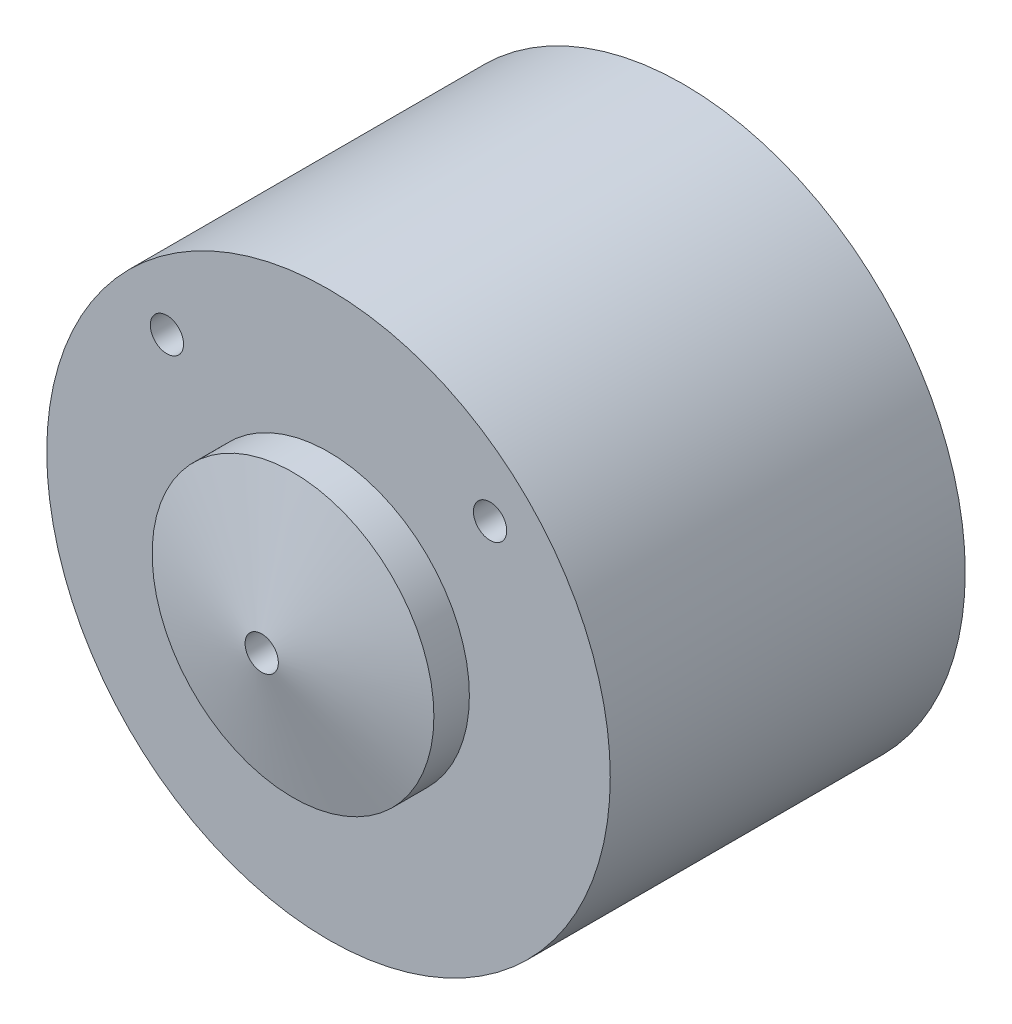
SolidWorks part; units mm, degrees
ref_plane "Спереди" through (0, 0, 0) normal (0, 0, 1) x (1, 0, 0)
ref_plane "Сверху" through (0, 0, 0) normal (0, 1, 0) x (1, 0, 0)
ref_plane "Справа" through (0, 0, 0) normal (1, 0, 0) x (0, 0, -1)
sketch "Эскиз1" plane through (0, 0, 0) normal (0, 0, 1) x (1, 0, 0)
  circle A0 centre (0, 0) radius 12.7
  dimension "D1" = 25.4
extrude "Бобышка-Вытянуть1" add sketch "Эскиз1" along normal blind 16
sketch "Эскиз2" plane through (0, 0, 16) normal (0, 0, 1) x (1, 0, 0)
  circle A0 centre (0, 0) radius 6.35
  dimension "D1" = 12.7
extrude "Бобышка-Вытянуть2" add sketch "Эскиз2" along normal blind 1.6
sketch "Эскиз3" plane through (0, 0, 17.6) normal (0, 0, 1) x (1, 0, 0)
  circle A0 centre (0, 0) radius 6.35
extrude "Бобышка-Вытянуть3" add sketch "Эскиз3" along normal blind 1.6 draft 75.857
sketch "Эскиз4" plane through (0, 0, 16) normal (0, 0, 1) x (1, 0, 0)
  circle A0 centre (0, 0) radius 0.75
  dimension "D1" = 1.5
extrude "Вырез-Вытянуть1" cut sketch "Эскиз4" against normal through all and the other way through all
sketch "Эскиз5" plane through (0, 0, 0) normal (0, 0, 1) x (1, 0, 0)
  line L0 (0, 0) -> (11.8467, 11.8467) construction
  line L1 (0, 0) -> (-12.914, 12.914) construction
  line L2 (0, 0) -> (0, 15.4863) construction
  circle A0 centre (0, 0) radius 10.3 construction
  circle A1 centre (-7.2832, 7.2832) radius 0.75
  circle A2 centre (7.2832, 7.2832) radius 0.75
  dimension "D3" = 20.6
  dimension "D4" = 1.5
  dimension "D1" = 45
  dimension "D2" = 90
extrude "Вырез-Вытянуть5" cut sketch "Эскиз5" along normal through all contours A2 | A1
